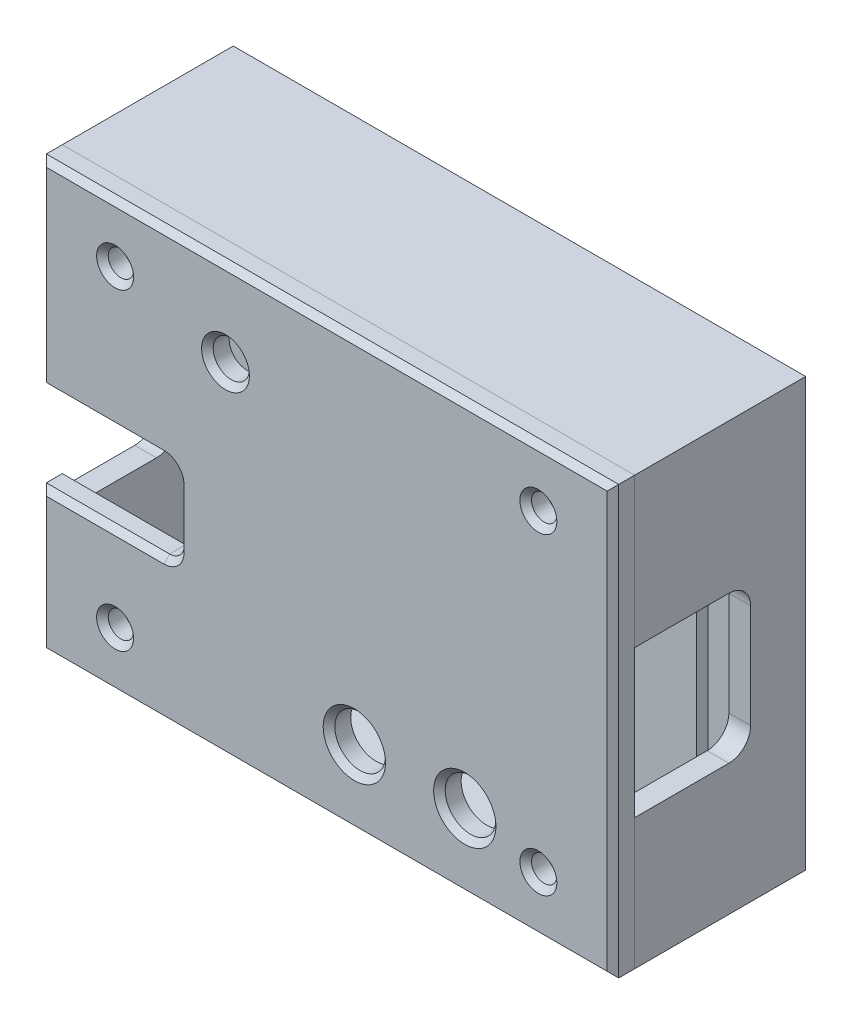
SolidWorks part; units mm, degrees
other "Lid"
other "Box"
other "PCB"
ref_plane "Front Plane" through (0, 0, 0) normal (0, 0, 1) x (1, 0, 0)
ref_plane "Top Plane" through (0, 0, 0) normal (0, 1, 0) x (1, 0, 0)
ref_plane "Right Plane" through (0, 0, 0) normal (1, 0, 0) x (0, 0, -1)
sketch "Sketch1" plane through (0, 0, 0) normal (0, 0, 1) x (1, 0, 0)
  line L0 (-29.21, -21.59) -> (-26.67, -21.59) construction
  line L1 (-35, -25) -> (35, -25)
  line L2 (-35, -25) -> (-35, 25)
  line L3 (-35, 25) -> (35, 25)
  line L4 (35, -25) -> (35, 25)
  line L5 (0, 25) -> (0, -25) construction
  line L6 (-35, 0) -> (35, 0) construction
  line L7 (-29.21, -21.59) -> (-29.21, -19.05) construction
  line L8 (-26.67, 21.59) -> (-26.67, 25) construction
  line L9 (-26.67, -21.59) -> (-26.67, -25) construction
  line L10 (-29.21, 19.05) -> (-35, 19.05) construction
  line L11 (29.21, 19.05) -> (35, 19.05) construction
  line L12 (-29.21, -13.97) -> (-27.94, -13.97) construction
  line L13 (-30.48, -12.7) -> (0.12, -12.7) construction
  line L14 (-30.48, -12.7) -> (-30.48, 5.08) construction
  line L15 (-30.48, 5.08) -> (0.12, 5.08) construction
  line L16 (0.12, -12.7) -> (0.12, 5.08) construction
  line L17 (-15.18, 5.08) -> (-15.18, -12.7) construction
  line L18 (-30.48, -3.81) -> (0.12, -3.81) construction
  line L19 (-27.94, -13.97) -> (-26.67, -13.97) construction
  line L21 (-29.21, -13.97) -> (-30.48, -13.97) construction
  circle A0 centre (-29.21, 21.59) radius 1.4
  circle A1 centre (29.21, 21.59) radius 1.4
  circle A2 centre (-29.21, -21.59) radius 1.4
  circle A3 centre (29.21, -21.59) radius 1.4
  point P0 (0, 0)
  point P4 (-29.21, -21.59)
  point P7 (-26.67, -21.59)
  point P8 (-24.13, -21.59)
  point P9 (-21.59, -21.59)
  point P10 (-19.05, -21.59)
  point P11 (-16.51, -21.59)
  point P12 (-13.97, -21.59)
  point P13 (-11.43, -21.59)
  point P14 (-8.89, -21.59)
  point P15 (-6.35, -21.59)
  point P16 (-3.81, -21.59)
  point P17 (-1.27, -21.59)
  point P18 (1.27, -21.59)
  point P19 (3.81, -21.59)
  point P20 (6.35, -21.59)
  point P21 (8.89, -21.59)
  point P22 (11.43, -21.59)
  point P23 (13.97, -21.59)
  point P24 (16.51, -21.59)
  point P25 (19.05, -21.59)
  point P26 (21.59, -21.59)
  point P27 (24.13, -21.59)
  point P28 (26.67, -21.59)
  point P29 (29.21, -21.59)
  point P30 (-26.67, -19.05)
  point P31 (-24.13, -19.05)
  point P32 (-21.59, -19.05)
  point P33 (-19.05, -19.05)
  point P34 (-16.51, -19.05)
  point P35 (-13.97, -19.05)
  point P36 (-11.43, -19.05)
  point P37 (-8.89, -19.05)
  point P38 (-6.35, -19.05)
  point P39 (-3.81, -19.05)
  point P40 (-1.27, -19.05)
  point P41 (1.27, -19.05)
  point P42 (3.81, -19.05)
  point P43 (6.35, -19.05)
  point P44 (8.89, -19.05)
  point P45 (11.43, -19.05)
  point P46 (13.97, -19.05)
  point P47 (16.51, -19.05)
  point P48 (19.05, -19.05)
  point P49 (21.59, -19.05)
  point P50 (24.13, -19.05)
  point P51 (26.67, -19.05)
  point P52 (29.21, -19.05)
  point P53 (-26.67, -16.51)
  point P54 (-24.13, -16.51)
  point P55 (-21.59, -16.51)
  point P56 (-19.05, -16.51)
  point P57 (-16.51, -16.51)
  point P58 (-13.97, -16.51)
  point P59 (-11.43, -16.51)
  point P60 (-8.89, -16.51)
  point P61 (-6.35, -16.51)
  point P62 (-3.81, -16.51)
  point P63 (-1.27, -16.51)
  point P64 (1.27, -16.51)
  point P65 (3.81, -16.51)
  point P66 (6.35, -16.51)
  point P67 (8.89, -16.51)
  point P68 (11.43, -16.51)
  point P69 (13.97, -16.51)
  point P70 (16.51, -16.51)
  point P71 (19.05, -16.51)
  point P72 (21.59, -16.51)
  point P73 (24.13, -16.51)
  point P74 (26.67, -16.51)
  point P75 (29.21, -16.51)
  point P76 (-26.67, -13.97)
  point P77 (-24.13, -13.97)
  point P78 (-21.59, -13.97)
  point P79 (-19.05, -13.97)
  point P80 (-16.51, -13.97)
  point P81 (-13.97, -13.97)
  point P82 (-11.43, -13.97)
  point P83 (-8.89, -13.97)
  point P84 (-6.35, -13.97)
  point P85 (-3.81, -13.97)
  point P86 (-1.27, -13.97)
  point P87 (1.27, -13.97)
  point P88 (3.81, -13.97)
  point P89 (6.35, -13.97)
  point P90 (8.89, -13.97)
  point P91 (11.43, -13.97)
  point P92 (13.97, -13.97)
  point P93 (16.51, -13.97)
  point P94 (19.05, -13.97)
  point P95 (21.59, -13.97)
  point P96 (24.13, -13.97)
  point P97 (26.67, -13.97)
  point P98 (29.21, -13.97)
  point P99 (-26.67, -11.43)
  point P100 (-24.13, -11.43)
  point P101 (-21.59, -11.43)
  point P102 (-19.05, -11.43)
  point P103 (-16.51, -11.43)
  point P104 (-13.97, -11.43)
  point P105 (-11.43, -11.43)
  point P106 (-8.89, -11.43)
  point P107 (-6.35, -11.43)
  point P108 (-3.81, -11.43)
  point P109 (-1.27, -11.43)
  point P110 (1.27, -11.43)
  point P111 (3.81, -11.43)
  point P112 (6.35, -11.43)
  point P113 (8.89, -11.43)
  point P114 (11.43, -11.43)
  point P115 (13.97, -11.43)
  point P116 (16.51, -11.43)
  point P117 (19.05, -11.43)
  point P118 (21.59, -11.43)
  point P119 (24.13, -11.43)
  point P120 (26.67, -11.43)
  point P121 (29.21, -11.43)
  point P122 (-26.67, -8.89)
  point P123 (-24.13, -8.89)
  point P124 (-21.59, -8.89)
  point P125 (-19.05, -8.89)
  point P126 (-16.51, -8.89)
  point P127 (-13.97, -8.89)
  point P128 (-11.43, -8.89)
  point P129 (-8.89, -8.89)
  point P130 (-6.35, -8.89)
  point P131 (-3.81, -8.89)
  point P132 (-1.27, -8.89)
  point P133 (1.27, -8.89)
  point P134 (3.81, -8.89)
  point P135 (6.35, -8.89)
  point P136 (8.89, -8.89)
  point P137 (11.43, -8.89)
  point P138 (13.97, -8.89)
  point P139 (16.51, -8.89)
  point P140 (19.05, -8.89)
  point P141 (21.59, -8.89)
  point P142 (24.13, -8.89)
  point P143 (26.67, -8.89)
  point P144 (29.21, -8.89)
  point P145 (-26.67, -6.35)
  point P146 (-24.13, -6.35)
  point P147 (-21.59, -6.35)
  point P148 (-19.05, -6.35)
  point P149 (-16.51, -6.35)
  point P150 (-13.97, -6.35)
  point P151 (-11.43, -6.35)
  point P152 (-8.89, -6.35)
  point P153 (-6.35, -6.35)
  point P154 (-3.81, -6.35)
  point P155 (-1.27, -6.35)
  point P156 (1.27, -6.35)
  point P157 (3.81, -6.35)
  point P158 (6.35, -6.35)
  point P159 (8.89, -6.35)
  point P160 (11.43, -6.35)
  point P161 (13.97, -6.35)
  point P162 (16.51, -6.35)
  point P163 (19.05, -6.35)
  point P164 (21.59, -6.35)
  point P165 (24.13, -6.35)
  point P166 (26.67, -6.35)
  point P167 (29.21, -6.35)
  point P168 (-26.67, -3.81)
  point P169 (-24.13, -3.81)
  point P170 (-21.59, -3.81)
  point P171 (-19.05, -3.81)
  point P172 (-16.51, -3.81)
  point P173 (-13.97, -3.81)
  point P174 (-11.43, -3.81)
  point P175 (-8.89, -3.81)
  point P176 (-6.35, -3.81)
  point P177 (-3.81, -3.81)
  point P178 (-1.27, -3.81)
  point P179 (1.27, -3.81)
  point P180 (3.81, -3.81)
  point P181 (6.35, -3.81)
  point P182 (8.89, -3.81)
  point P183 (11.43, -3.81)
  point P184 (13.97, -3.81)
  point P185 (16.51, -3.81)
  point P186 (19.05, -3.81)
  point P187 (21.59, -3.81)
  point P188 (24.13, -3.81)
  point P189 (26.67, -3.81)
  point P190 (29.21, -3.81)
  point P191 (-26.67, -1.27)
  point P192 (-24.13, -1.27)
  point P193 (-21.59, -1.27)
  point P194 (-19.05, -1.27)
  point P195 (-16.51, -1.27)
  point P196 (-13.97, -1.27)
  point P197 (-11.43, -1.27)
  point P198 (-8.89, -1.27)
  point P199 (-6.35, -1.27)
  point P200 (-3.81, -1.27)
  point P201 (-1.27, -1.27)
  point P202 (1.27, -1.27)
  point P203 (3.81, -1.27)
  point P204 (6.35, -1.27)
  point P205 (8.89, -1.27)
  point P206 (11.43, -1.27)
  point P207 (13.97, -1.27)
  point P208 (16.51, -1.27)
  point P209 (19.05, -1.27)
  point P210 (21.59, -1.27)
  point P211 (24.13, -1.27)
  point P212 (26.67, -1.27)
  point P213 (29.21, -1.27)
  point P214 (-26.67, 1.27)
  point P215 (-24.13, 1.27)
  point P216 (-21.59, 1.27)
  point P217 (-19.05, 1.27)
  point P218 (-16.51, 1.27)
  point P219 (-13.97, 1.27)
  point P220 (-11.43, 1.27)
  point P221 (-8.89, 1.27)
  point P222 (-6.35, 1.27)
  point P223 (-3.81, 1.27)
  point P224 (-1.27, 1.27)
  point P225 (1.27, 1.27)
  point P226 (3.81, 1.27)
  point P227 (6.35, 1.27)
  point P228 (8.89, 1.27)
  point P229 (11.43, 1.27)
  point P230 (13.97, 1.27)
  point P231 (16.51, 1.27)
  point P238 (19.05, 1.27)
  point P239 (21.59, 1.27)
  point P240 (24.13, 1.27)
  point P241 (26.67, 1.27)
  point P242 (29.21, 1.27)
  point P243 (-26.67, 3.81)
  point P244 (-24.13, 3.81)
  point P245 (-21.59, 3.81)
  point P246 (-19.05, 3.81)
  point P247 (-16.51, 3.81)
  point P248 (-13.97, 3.81)
  point P249 (-11.43, 3.81)
  point P250 (-8.89, 3.81)
  point P251 (-6.35, 3.81)
  point P252 (-3.81, 3.81)
  point P253 (-1.27, 3.81)
  point P254 (1.27, 3.81)
  point P255 (3.81, 3.81)
  point P256 (6.35, 3.81)
  point P257 (8.89, 3.81)
  point P258 (11.43, 3.81)
  point P259 (13.97, 3.81)
  point P260 (16.51, 3.81)
  point P261 (19.05, 3.81)
  point P262 (21.59, 3.81)
  point P263 (24.13, 3.81)
  point P264 (26.67, 3.81)
  point P265 (29.21, 3.81)
  point P266 (-26.67, 6.35)
  point P267 (-24.13, 6.35)
  point P268 (-21.59, 6.35)
  point P269 (-19.05, 6.35)
  point P270 (-16.51, 6.35)
  point P271 (-13.97, 6.35)
  point P272 (-11.43, 6.35)
  point P273 (-8.89, 6.35)
  point P274 (-6.35, 6.35)
  point P275 (-3.81, 6.35)
  point P276 (-1.27, 6.35)
  point P277 (1.27, 6.35)
  point P278 (3.81, 6.35)
  point P279 (6.35, 6.35)
  point P280 (8.89, 6.35)
  point P281 (11.43, 6.35)
  point P282 (13.97, 6.35)
  point P283 (16.51, 6.35)
  point P284 (19.05, 6.35)
  point P285 (21.59, 6.35)
  point P286 (24.13, 6.35)
  point P287 (26.67, 6.35)
  point P288 (29.21, 6.35)
  point P289 (-26.67, 8.89)
  point P290 (-24.13, 8.89)
  point P291 (-21.59, 8.89)
  point P292 (-19.05, 8.89)
  point P293 (-16.51, 8.89)
  point P294 (-13.97, 8.89)
  point P295 (-11.43, 8.89)
  point P296 (-8.89, 8.89)
  point P297 (-6.35, 8.89)
  point P298 (-3.81, 8.89)
  point P299 (-1.27, 8.89)
  point P300 (1.27, 8.89)
  point P301 (3.81, 8.89)
  point P302 (6.35, 8.89)
  point P303 (8.89, 8.89)
  point P304 (11.43, 8.89)
  point P305 (13.97, 8.89)
  point P306 (16.51, 8.89)
  point P307 (19.05, 8.89)
  point P308 (21.59, 8.89)
  point P309 (24.13, 8.89)
  point P310 (26.67, 8.89)
  point P311 (29.21, 8.89)
  point P312 (-26.67, 11.43)
  point P313 (-24.13, 11.43)
  point P314 (-21.59, 11.43)
  point P315 (-19.05, 11.43)
  point P316 (-16.51, 11.43)
  point P317 (-13.97, 11.43)
  point P318 (-11.43, 11.43)
  point P319 (-8.89, 11.43)
  point P320 (-6.35, 11.43)
  point P321 (-3.81, 11.43)
  point P322 (-1.27, 11.43)
  point P323 (1.27, 11.43)
  point P324 (3.81, 11.43)
  point P325 (6.35, 11.43)
  point P326 (8.89, 11.43)
  point P327 (11.43, 11.43)
  point P328 (13.97, 11.43)
  point P329 (16.51, 11.43)
  point P330 (19.05, 11.43)
  point P331 (21.59, 11.43)
  point P332 (24.13, 11.43)
  point P333 (26.67, 11.43)
  point P334 (29.21, 11.43)
  point P335 (-26.67, 13.97)
  point P336 (-24.13, 13.97)
  point P337 (-21.59, 13.97)
  point P338 (-19.05, 13.97)
  point P339 (-16.51, 13.97)
  point P340 (-13.97, 13.97)
  point P341 (-11.43, 13.97)
  point P342 (-8.89, 13.97)
  point P343 (-6.35, 13.97)
  point P344 (-3.81, 13.97)
  point P345 (-1.27, 13.97)
  point P346 (1.27, 13.97)
  point P347 (3.81, 13.97)
  point P348 (6.35, 13.97)
  point P349 (8.89, 13.97)
  point P350 (11.43, 13.97)
  point P351 (13.97, 13.97)
  point P352 (16.51, 13.97)
  point P353 (19.05, 13.97)
  point P354 (21.59, 13.97)
  point P355 (24.13, 13.97)
  point P356 (26.67, 13.97)
  point P357 (29.21, 13.97)
  point P358 (-26.67, 16.51)
  point P359 (-24.13, 16.51)
  point P360 (-21.59, 16.51)
  point P361 (-19.05, 16.51)
  point P362 (-16.51, 16.51)
  point P363 (-13.97, 16.51)
  point P364 (-11.43, 16.51)
  point P365 (-8.89, 16.51)
  point P366 (-6.35, 16.51)
  point P367 (-3.81, 16.51)
  point P368 (-1.27, 16.51)
  point P369 (1.27, 16.51)
  point P370 (3.81, 16.51)
  point P371 (6.35, 16.51)
  point P372 (8.89, 16.51)
  point P373 (11.43, 16.51)
  point P374 (13.97, 16.51)
  point P375 (16.51, 16.51)
  point P376 (19.05, 16.51)
  point P377 (21.59, 16.51)
  point P378 (24.13, 16.51)
  point P379 (26.67, 16.51)
  point P380 (29.21, 16.51)
  point P381 (-26.67, 19.05)
  point P382 (-24.13, 19.05)
  point P383 (-21.59, 19.05)
  point P384 (-19.05, 19.05)
  point P385 (-16.51, 19.05)
  point P386 (-13.97, 19.05)
  point P387 (-11.43, 19.05)
  point P388 (-8.89, 19.05)
  point P389 (-6.35, 19.05)
  point P390 (-3.81, 19.05)
  point P391 (-1.27, 19.05)
  point P392 (1.27, 19.05)
  point P393 (3.81, 19.05)
  point P394 (6.35, 19.05)
  point P395 (8.89, 19.05)
  point P396 (11.43, 19.05)
  point P397 (13.97, 19.05)
  point P398 (16.51, 19.05)
  point P399 (19.05, 19.05)
  point P400 (21.59, 19.05)
  point P401 (24.13, 19.05)
  point P402 (26.67, 19.05)
  point P403 (29.21, 19.05)
  point P404 (-26.67, 21.59)
  point P405 (-24.13, 21.59)
  point P406 (-21.59, 21.59)
  point P407 (-19.05, 21.59)
  point P408 (-16.51, 21.59)
  point P409 (-13.97, 21.59)
  point P410 (-11.43, 21.59)
  point P411 (-8.89, 21.59)
  point P412 (-6.35, 21.59)
  point P413 (-3.81, 21.59)
  point P414 (-1.27, 21.59)
  point P415 (1.27, 21.59)
  point P416 (3.81, 21.59)
  point P417 (6.35, 21.59)
  point P418 (8.89, 21.59)
  point P419 (11.43, 21.59)
  point P420 (13.97, 21.59)
  point P421 (16.51, 21.59)
  point P422 (19.05, 21.59)
  point P423 (21.59, 21.59)
  point P424 (24.13, 21.59)
  point P425 (26.67, 21.59)
  point P426 (29.21, 21.59)
  point P427 (-29.21, -19.05)
  point P428 (-29.21, -16.51)
  point P429 (-29.21, -13.97)
  point P430 (-29.21, -11.43)
  point P431 (-29.21, -8.89)
  point P432 (-29.21, -6.35)
  point P433 (-29.21, -3.81)
  point P434 (-29.21, -1.27)
  point P435 (-29.21, 1.27)
  point P436 (-29.21, 3.81)
  point P437 (-29.21, 6.35)
  point P438 (-29.21, 8.89)
  point P439 (-29.21, 11.43)
  point P440 (-29.21, 13.97)
  point P441 (-29.21, 16.51)
  point P442 (-29.21, 19.05)
  point P443 (-29.21, 21.59)
  point P459 (-15.18, -3.81)
  point P466 (0, 0)
  dimension "D6" = 2.8
  dimension "D1" = 70
  dimension "D2" = 50
  dimension "D5" = 2.54
  dimension "D7" = 30.6
  dimension "D8" = 17.78
  dimension "D3" = 24
  dimension "D4" = 18
extrude "Boss-Extrude1" add sketch "Sketch1" along normal blind 1.6
ref_plane "Plane1" through (0, 0, -6) normal (0, 0, 1) x (1, 0, 0)
sketch "Sketch2" plane through (0, 0, -6) normal (0, 0, 1) x (1, 0, 0)
  line L0 (35, -25) -> (35, 25) construction
  line L1 (-35, -25) -> (35, -25) construction
  line L2 (-35, 25) -> (35, 25) construction
  line L3 (-35, -25) -> (-35, 25) construction
  line L4 (35, -25) -> (35, 25) construction
  line L5 (-35, -25) -> (35, -25) construction
  line L6 (-35, 25) -> (35, 25) construction
  line L7 (-35, -25) -> (-35, 25) construction
  line L8 (36.5, -26.5) -> (36.5, 26.5)
  line L9 (-36.5, 26.5) -> (36.5, 26.5)
  line L10 (-36.5, -26.5) -> (-36.5, 26.5)
  line L11 (-36.5, -26.5) -> (36.5, -26.5)
  circle A0 centre (29.21, 21.59) radius 1.4 construction
  circle A1 centre (29.21, -21.59) radius 1.4 construction
  circle A2 centre (-29.21, -21.59) radius 1.4 construction
  circle A3 centre (-29.21, 21.59) radius 1.4 construction
  circle A4 centre (29.21, 21.59) radius 1.4
  circle A5 centre (29.21, -21.59) radius 1.4
  circle A6 centre (-29.21, -21.59) radius 1.4
  circle A7 centre (-29.21, 21.59) radius 1.4
  dimension "D1" = 1.5
extrude "Boss-Extrude2" add sketch "Sketch2" against normal blind 3 separate body
sketch "Sketch3" plane through (0, 0, -9) normal (0, 0, -1) x (-1, 0, 0)
  line L0 (-39.5, 29.5) -> (-39.5, -29.5)
  line L1 (-39.5, -29.5) -> (39.5, -29.5)
  line L2 (39.5, -29.5) -> (39.5, 29.5)
  line L3 (39.5, 29.5) -> (-39.5, 29.5)
  line L4 (-36.5, 26.5) -> (-36.5, -26.5)
  line L5 (36.5, 26.5) -> (-36.5, 26.5)
  line L6 (36.5, -26.5) -> (36.5, 26.5)
  line L7 (-36.5, -26.5) -> (36.5, -26.5)
  line L8 (-36.5, 26.5) -> (-36.5, -26.5)
  line L9 (36.5, 26.5) -> (-36.5, 26.5)
  line L10 (36.5, -26.5) -> (36.5, 26.5)
  line L11 (-36.5, -26.5) -> (36.5, -26.5)
  dimension "D1" = 0
  dimension "D2" = 3
extrude "Boss-Extrude3" add sketch "Sketch3" against normal offset from surface (23.6 mm away) 13 up to face at (0, 0, 1.6) offset beyond the face yes
sketch "Sketch4" plane through (0, 0, 14.6) normal (0, 0, 1) x (1, 0, 0)
  line L0 (-39.5, -29.5) -> (-39.5, 29.5) construction
  line L1 (39.5, -29.5) -> (-39.5, -29.5) construction
  line L2 (-39.5, -29.5) -> (-39.5, 29.5)
  line L3 (39.5, -29.5) -> (-39.5, -29.5)
  line L4 (39.5, 29.5) -> (39.5, -29.5) construction
  line L5 (-39.5, 29.5) -> (39.5, 29.5) construction
  line L6 (39.5, 29.5) -> (39.5, -29.5)
  line L7 (-39.5, 29.5) -> (39.5, 29.5)
  circle A0 centre (29.21, 21.59) radius 1.4 construction
  circle A1 centre (-29.21, 21.59) radius 1.4 construction
  circle A2 centre (-29.21, -21.59) radius 1.4 construction
  circle A3 centre (29.21, -21.59) radius 1.4 construction
  circle A4 centre (29.21, 21.59) radius 1.4 construction
  circle A5 centre (-29.21, 21.59) radius 1.4 construction
  circle A6 centre (-29.21, -21.59) radius 1.4 construction
  circle A7 centre (29.21, -21.59) radius 1.4 construction
  circle A8 centre (-29.21, 21.59) radius 1.75
  circle A9 centre (29.21, 21.59) radius 1.75
  circle A10 centre (29.21, -21.59) radius 1.75
  circle A11 centre (-29.21, -21.59) radius 1.75
  dimension "D1" = 3.5
extrude "Boss-Extrude4" add sketch "Sketch4" along normal blind 3 separate body
ref_plane "Plane2" through (0, 0, 4.01) normal (0, 0, 1) x (1, 0, 0)
ref_plane "Plane3" through (0, 0, 5.79) normal (0, 0, 1) x (1, 0, 0)
ref_plane "Plane4" through (0, 0, 7.39) normal (0, 0, 1) x (1, 0, 0)
sketch "Sketch5" plane through (0, 0, 17.6) normal (0, 0, 1) x (1, 0, 0)
  line L0 (-30.48, -3.81) -> (0.12, -3.81) construction
  line L1 (3.81, -11.43) -> (-39.5, -11.43)
  line L2 (3.81, -11.43) -> (3.81, 3.81)
  line L3 (3.81, 3.81) -> (-39.5, 3.81)
  line L4 (-39.5, -11.43) -> (-39.5, 3.81)
  line L5 (-17.845, 3.81) -> (-17.845, -11.43) construction
  line L6 (3.81, -3.81) -> (-39.5, -3.81) construction
  line L7 (-39.5, -29.5) -> (-39.5, 29.5) construction
  point P0 (-17.845, -3.81)
extrude "Cut-Extrude1" [suppressed] cut sketch "Sketch5" against normal up to surface (9 mm away)
sketch "Sketch6" plane through (0, 0, 17.6) normal (0, 0, 1) x (1, 0, 0)
  line L0 (-37.37, 11.43) -> (-29.67, 11.43) construction
  line L1 (-29.67, 11.43) -> (-23.67, 11.43) construction
  line L2 (-26.67, 6.73) -> (-26.67, 11.43) construction
  line L3 (3.81, 3.81) -> (-39.5, 3.81) construction
  line L4 (-39.5, 16.13) -> (-21.59, 16.13)
  line L5 (-39.5, 16.13) -> (-39.5, 3.81)
  line L6 (-39.5, 3.81) -> (-21.59, 3.81)
  line L7 (-21.59, 16.13) -> (-21.59, 3.81)
  line L8 (-39.5, -29.5) -> (-39.5, 29.5) construction
  circle A0 centre (-26.67, 6.73) radius 0.5 construction
  circle A1 centre (-29.67, 11.43) radius 0.5 construction
  circle A2 centre (-23.67, 11.43) radius 0.5 construction
  point P6 (-37.37, 11.43)
  dimension "D4" = 1
  dimension "D1" = 4.7
  dimension "D2" = 6
  dimension "D3" = 10.7
  dimension "D5" = 4.7
extrude "Cut-Extrude2" [suppressed] cut sketch "Sketch6" against normal up to surface (9 mm away)
fillet "Fillet2" [suppressed] radius 3
sketch "Sketch9" plane through (0, 0, 14.6) normal (0, 0, 1) x (1, 0, 0)
  line L0 (-39.5, 16.13) -> (-21.59, 16.13) construction
  line L1 (-39.5, 16.13) -> (-36.5, 16.13)
  line L2 (-39.5, 16.13) -> (-39.5, -11.43)
  line L3 (-39.5, -11.43) -> (-36.5, -11.43)
  line L4 (-36.5, 16.13) -> (-36.5, -11.43)
  line L5 (-39.5, -29.5) -> (-39.5, 29.5) construction
  line L6 (3.81, -11.43) -> (-39.5, -11.43) construction
  line L7 (-36.5, -26.5) -> (-36.5, 26.5) construction
extrude "Cut-Extrude5" cut sketch "Sketch9" against normal up to surface (13 mm away) up to face at (0, 0, 1.6)
sketch "Sketch7" plane through (0, 0, 1.6) normal (0, 0, 1) x (1, 0, 0)
  line L0 (-13.97, 19.05) -> (-13.97, 16.51) construction
  circle A0 centre (3.81, -19.05) radius 3.5
  circle A1 centre (19.05, -19.05) radius 3.5
  circle A2 centre (-13.97, 17.78) radius 2.5
  circle A3 centre (-4.81, 0.682) radius 2 construction
  point P3 (-4.81, 0.682)
  dimension "D1" = 7
  dimension "D2" = 5
  dimension "D3" = 4
  dimension "D5" = 1
extrude "Cut-Extrude3" cut sketch "Sketch7" along normal through all
sketch "Sketch8" plane through (0, 0, 14.6) normal (0, 0, 1) x (1, 0, 0)
  line L0 (39.5, 29.5) -> (39.5, -29.5) construction
  line L1 (39.5, 8.89) -> (35, 8.89)
  line L2 (39.5, 8.89) -> (39.5, -11.43)
  line L3 (39.5, -11.43) -> (35, -11.43)
  line L4 (35, 8.89) -> (35, -11.43)
  line L5 (35, -25) -> (35, 25) construction
extrude "Cut-Extrude4" cut sketch "Sketch8" against normal offset from surface (16 mm away) 3 up to face at (0, 0, 1.6) offset beyond the face yes
fillet "Fillet3" radius 3 4 edges at (38, -11.43, -1.4) (38, 8.89, -1.4) (-38, -11.43, 1.6) (-38, 16.13, 1.6)
fillet "Fillet4" radius 3 8 edges at (-36.5, -26.5, 4.3) (-36.5, 26.5, 4.3) (36.5, 26.5, 4.3) (36.5, -26.5, 4.3) (0, -26.5, -6) (36.5, 0, -6) (-36.5, 0, -6) (0, 26.5, -6)
sketch "Sketch10" plane through (0, 0, 17.6) normal (0, 0, 1) x (1, 0, 0)
  line L0 (-30.48, -3.81) -> (0.12, -3.81) construction
  line L1 (-39.5, -9.81) -> (-20.48, -9.81)
  line L2 (-39.5, -9.81) -> (-39.5, 2.19)
  line L3 (-39.5, 2.19) -> (-20.48, 2.19)
  line L4 (-20.48, -9.81) -> (-20.48, 2.19)
  line L5 (-29.99, 2.19) -> (-29.99, -9.81) construction
  line L6 (-39.5, -3.81) -> (-20.48, -3.81) construction
  line L7 (-39.5, -11.43) -> (-39.5, 3.81) construction
  line L8 (-30.48, -12.7) -> (-30.48, 5.08) construction
  point P0 (-29.99, -3.81)
  dimension "D1" = 10
  dimension "D2" = 12
extrude "Cut-Extrude6" cut sketch "Sketch10" against normal through all
fillet "Fillet5" radius 2 2 edges at (-20.48, -9.81, 16.1) (-20.48, 2.19, 16.1)
chamfer "Chamfer1" distance 0.8 angle 45 17 edges at (-39.5, 15.845, 17.6) (0, 29.5, 17.6) (39.5, 0, 17.6) (0, -29.5, 17.6) (-39.5, -19.655, 17.6) (-27.46, 21.59, 17.6) (30.96, 21.59, 17.6) (30.96, -21.59, 17.6) (-27.46, -21.59, 17.6) (22.55, -19.05, 17.6) (7.31, -19.05, 17.6) (-21.0658, 1.6042, 17.6) (-30.99, 2.19, 17.6) (-30.99, -9.81, 17.6) (-21.0658, -9.2242, 17.6) (-20.48, -3.81, 17.6) (-11.47, 17.78, 17.6)
